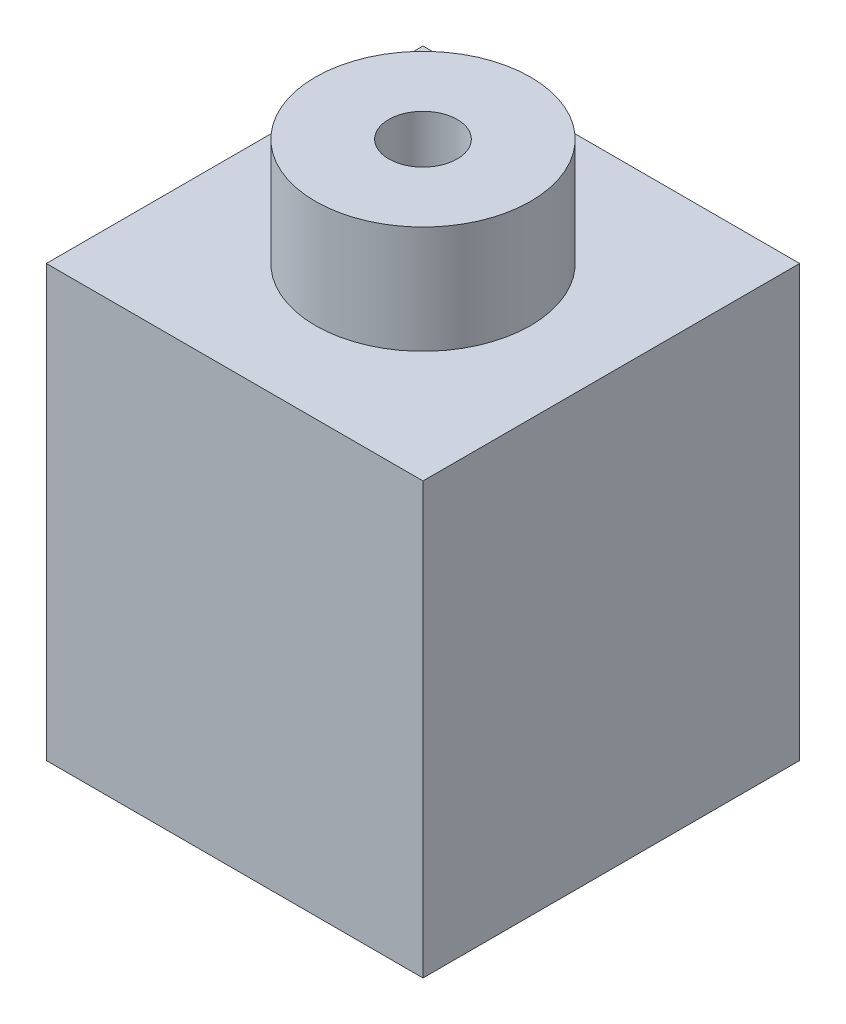
SolidWorks part; units mm, degrees
ref_plane "Front Plane" through (0, 0, 0) normal (0, 0, 1) x (1, 0, 0)
ref_plane "Top Plane" through (0, 0, 0) normal (0, 1, 0) x (1, 0, 0)
ref_plane "Right Plane" through (0, 0, 0) normal (1, 0, 0) x (0, 0, -1)
sketch "Sketch1" plane through (0, 0, 0) normal (0, 1, 0) x (1, 0, 0)
  line L1 (-11.1125, -11.1125) -> (11.1125, -11.1125)
  line L2 (-11.1125, -11.1125) -> (-11.1125, 11.1125)
  line L3 (-11.1125, 11.1125) -> (11.1125, 11.1125)
  line L4 (11.1125, -11.1125) -> (11.1125, 11.1125)
  line L5 (-11.1125, -11.1125) -> (11.1125, 11.1125) construction
  line L6 (-11.1125, 11.1125) -> (11.1125, -11.1125) construction
  point P0 (0, 0)
  dimension "D1" = 22.225
extrude "Boss-Extrude1" add sketch "Sketch1" along normal blind 25.4
sketch "Sketch2" plane through (0, 25.4, 0) normal (0, 1, 0) x (1, 0, 0)
  circle A0 centre (0, 0) radius 6.35
  dimension "D1" = 12.7
extrude "Boss-Extrude2" add sketch "Sketch2" along normal blind 6.35
sketch "Sketch3" plane through (0, 31.75, 0) normal (0, 1, 0) x (1, 0, 0)
  point P0 (0, 0)
hole_wizard "#10-32 Tapped Hole1" positions "Sketch5" profile "Sketch4" tap size "#10-32" standard "ANSI Inch" end condition through all
sketch "Sketch5" plane through (0, 31.75, 0) normal (0, 1, 0) x (1, 0, 0)
  point P0 (0, 0)
sketch "Sketch4" plane through (0, 31.75, 0) normal (1, 0, 0) x (0, 0, 1)
  line L0 (0, 0) -> (0, 31.75)
  line L1 (0, 31.75) -> (2.0193, 31.75)
  line L2 (2.0193, 31.75) -> (2.0193, 0)
  line L5 (2.0193, 0) -> (0, 0)
  line L11 (0, -6.35) -> (0, 107.95) construction
  dimension "Thru Tap Drill Dia." = 4.0386
  dimension "Thru Tap Drill Depth" = 31.75
cosmetic thread "Hole Thread1" parameters "D2"=4.826
sketch "Sketch6" plane through (0, 0, 0) normal (0, -1, 0) x (1, 0, 0)
  line L0 (11.1125, 11.1125) -> (11.1125, -11.1125) construction
  line L1 (-8.5725, -8.5725) -> (8.5725, -8.5725)
  line L2 (-8.5725, -8.5725) -> (-8.5725, 8.5725)
  line L3 (-8.5725, 8.5725) -> (8.5725, 8.5725)
  line L4 (8.5725, -8.5725) -> (8.5725, 8.5725)
  line L5 (-8.5725, -8.5725) -> (8.5725, 8.5725) construction
  line L6 (-8.5725, 8.5725) -> (8.5725, -8.5725) construction
  line L7 (-11.1125, 11.1125) -> (11.1125, 11.1125) construction
  circle A0 centre (0, 0) radius 5.1943
  circle A1 centre (0, 0) radius 2.0193 construction
  dimension "D1" = 3.175
  dimension "D2" = 2.54
  dimension "D3" = 2.54
extrude "Cut-Extrude1" cut sketch "Sketch6" against normal blind 21.59
sketch "Sketch7" plane through (0, 0, 0) normal (0, -1, 0) x (-1, 0, 0)
  line L1 (8.5725, 8.5725) -> (-8.5725, 8.5725)
  line L2 (8.5725, 8.5725) -> (8.5725, -8.5725)
  line L3 (8.5725, -8.5725) -> (-8.5725, -8.5725)
  line L4 (-8.5725, 8.5725) -> (-8.5725, -8.5725)
  circle A0 centre (0, 0) radius 5.1943
extrude "Boss-Extrude3" add sketch "Sketch7" against normal blind 3.81
